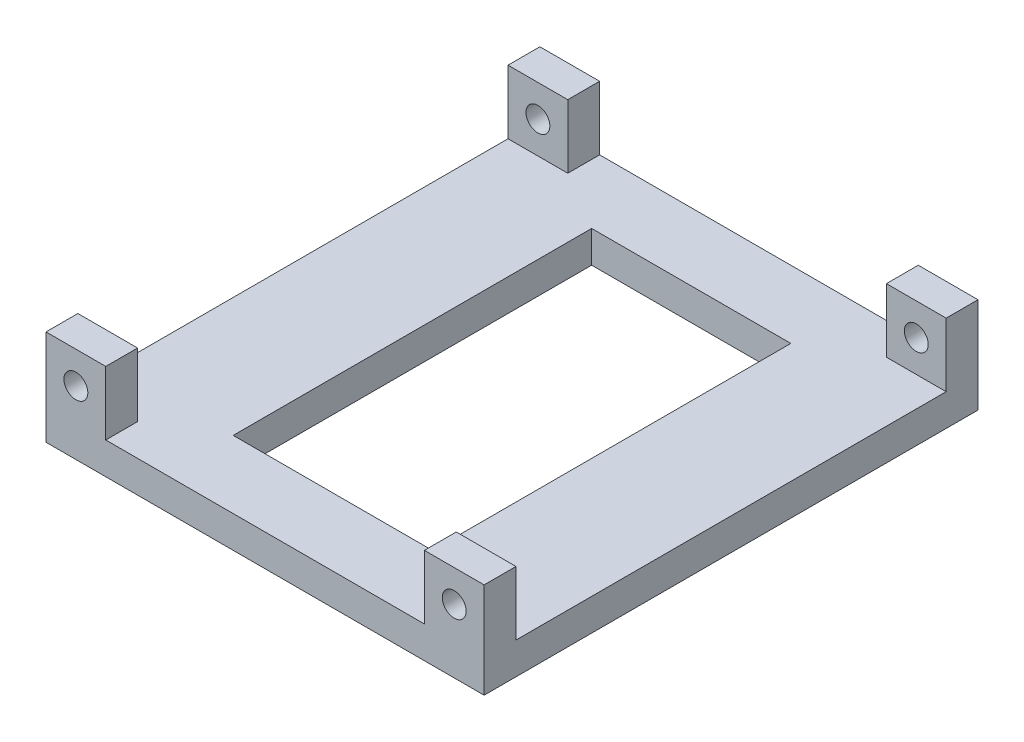
SolidWorks part; units mm, degrees
ref_plane "Front Plane" through (0, 0, 0) normal (0, 0, 1) x (1, 0, 0)
ref_plane "Top Plane" through (0, 0, 0) normal (0, 1, 0) x (1, 0, 0)
ref_plane "Right Plane" through (0, 0, 0) normal (1, 0, 0) x (0, 0, -1)
sketch "Sketch1" plane through (0, 0, 0) normal (0, 1, 0) x (1, 0, 0)
  line L1 (-27.5, 31) -> (27.5, 31)
  line L2 (-27.5, 31) -> (-27.5, -31)
  line L3 (-27.5, -31) -> (27.5, -31)
  line L4 (27.5, 31) -> (27.5, -31)
  line L5 (-27.5, 31) -> (27.5, -31) construction
  line L6 (-27.5, -31) -> (27.5, 31) construction
  line L7 (-12.5, 22.5) -> (12.5, 22.5)
  line L8 (-12.5, 22.5) -> (-12.5, -22.5)
  line L9 (-12.5, -22.5) -> (12.5, -22.5)
  line L10 (12.5, 22.5) -> (12.5, -22.5)
  line L11 (-12.5, 22.5) -> (12.5, -22.5) construction
  line L12 (-12.5, -22.5) -> (12.5, 22.5) construction
  point P0 (0, 0)
  point P6 (0, 0)
  dimension "D3" = 45
  dimension "D1" = 55
  dimension "D2" = 62
  dimension "D4" = 25
extrude "Boss-Extrude1" add sketch "Sketch1" along normal blind 4
sketch "Sketch2" plane through (0, 0, 31) normal (0, 0, 1) x (1, 0, 0)
  line L0 (0, 0) -> (0, 10.3471) construction
  line L1 (-27.5, 4) -> (-20, 4)
  line L2 (-27.5, 4) -> (-27.5, 12)
  line L3 (-27.5, 12) -> (-20, 12)
  line L4 (-20, 4) -> (-20, 12)
  line L5 (20, 4) -> (20, 12)
  line L6 (27.5, 12) -> (20, 12)
  line L7 (27.5, 4) -> (27.5, 12)
  line L8 (27.5, 4) -> (20, 4)
  circle A0 centre (-23.75, 8) radius 1.5
  circle A1 centre (23.75, 8) radius 1.5
  dimension "D3" = 3.75
  dimension "D4" = 4
  dimension "D1" = 8
  dimension "D2" = 7.5
extrude "Boss-Extrude2" add sketch "Sketch2" against normal blind 4
ref_plane "Plane1" through (0, 0, 0) normal (0, 0, 1) x (1, 0, 0)
mirror "Mirror1" about plane through (0, 0, 0) normal (0, 0, 1) of "Boss-Extrude2"
